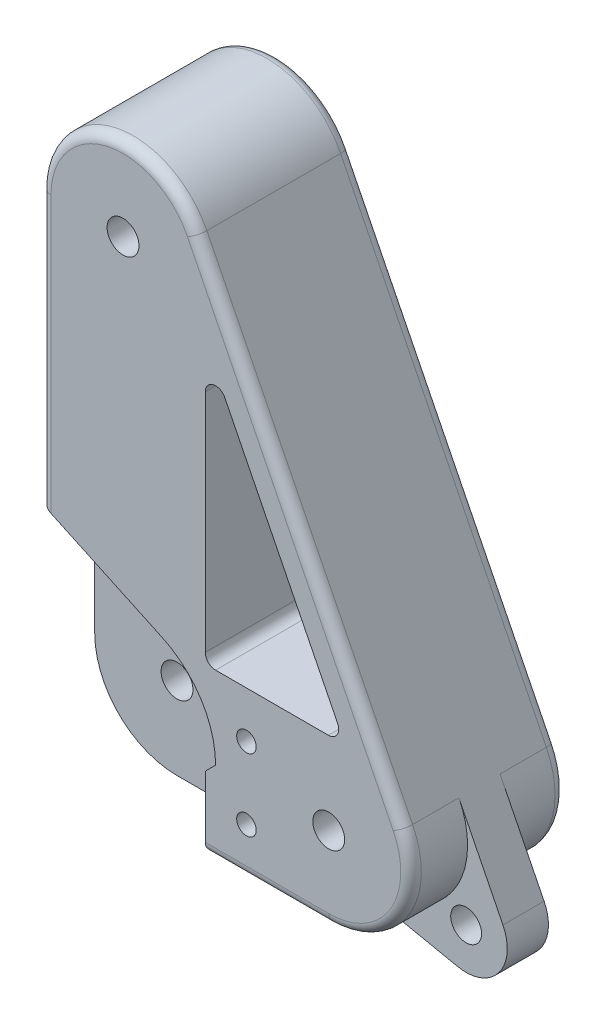
SolidWorks part; units mm, degrees
ref_plane "Front Plane" through (0, 0, 0) normal (0, 0, 1) x (1, 0, 0)
ref_plane "Top Plane" through (0, 0, 0) normal (0, 1, 0) x (1, 0, 0)
ref_plane "Right Plane" through (0, 0, 0) normal (1, 0, 0) x (0, 0, -1)
sketch "Sketch1" plane through (0, 0, 0) normal (0, 0, 1) x (1, 0, 0)
  line L2 (20, -8) -> (0, -8)
  line L3 (-8, 40) -> (-8, 0)
  line L4 (7.1554, 43.5777) -> (27.1554, 3.5777)
  circle A0 centre (0, 0) radius 1.55
  circle A1 centre (20, 0) radius 1.55
  circle A2 centre (0, 40) radius 1.55
  arc A3 (-8, 40) -> (7.1554, 43.5777) centre (0, 40) cw
  arc A4 (-8, 0) -> (0, -8) centre (0, 0) ccw
  arc A5 (27.1554, 3.5777) -> (20, -8) centre (20, 0) cw
  dimension "D1" = 3.1
  dimension "D2" = 8
  dimension "D3" = 40
  dimension "D5" = 20
extrude "Boss-Extrude1" add sketch "Sketch1" along normal blind 15
fillet "Fillet1" radius 1 6 edges at (26.8052, -4.2058, 0) (10, -8, 0) (-5.6569, -5.6569, 0) (-8, 20, 0) (-1.838, 47.786, 0) (17.1554, 23.5777, 0)
fillet "Fillet2" radius 1 6 edges at (-8, 20, 15) (-5.6569, -5.6569, 15) (10, -8, 15) (26.8052, -4.2058, 15) (-1.838, 47.786, 15) (17.1554, 23.5777, 15)
sketch "Sketch2" plane through (0, 0, 15) normal (0, 0, 1) x (1, 0, 0)
  line L2 (8, -8) -> (-8, -8)
  line L3 (-8, -8) -> (-8, 13.6609)
  line L4 (-8, 13.6609) -> (3.8036, 8.1568)
  line L5 (9, 0) -> (8, -8) construction
  line L6 (8, -8) -> (8, -1)
  line L7 (8, -1) -> (9, 0)
  line L8 (20, -8) -> (0, -8) construction
  line L9 (-8, 0) -> (-8, 40) construction
  arc A3 (3.8036, 8.1568) -> (9, 0) centre (0, 0) cw
  dimension "D1" = 9
  dimension "D2" = 1
  dimension "D3" = 25
  dimension "D4" = 45
extrude "Cut-Extrude1" cut sketch "Sketch2" against normal blind 5.25
ref_plane "Plane1" through (0, 0, 7.5) normal (0, 0, 1) x (1, 0, 0)
mirror "Mirror1" about plane through (0, 0, 7.5) normal (0, 0, 1) of "Cut-Extrude1"
sketch "Sketch3" plane through (0, 0, 7.5) normal (0, 0, 1) x (1, 0, 0)
  line L0 (31.4367, -4.9848) -> (27.1554, 3.5777)
  line L1 (27.1554, 3.5777) -> (14, -8)
  line L2 (7.1554, 43.5777) -> (27.1554, 3.5777) construction
  line L3 (14, -8) -> (27.0511, -10.6912)
  line L5 (20, -8) -> (8, -8) construction
  circle A0 centre (27.859, -6.7736) radius 1.5
  arc A1 (27.0511, -10.6912) -> (31.4367, -4.9848) centre (27.859, -6.7736) ccw
  dimension "D1" = 3
  dimension "D2" = 4
extrude "Boss-Extrude2" add sketch "Sketch3" against normal blind 2 and the other way blind 2
sketch "Sketch4" plane through (0, 0, 0) normal (0, 0, -1) x (-1, 0, 0)
  line L0 (0, 0) -> (-15.2179, 0) construction
  circle A0 centre (-12, 3.5) radius 0.95
  circle A2 centre (-12, -3.5) radius 0.95
  circle A3 centre (0, 0) radius 1.55 construction
  dimension "D1" = 1.9
  dimension "D2" = 7
  dimension "D3" = 12
extrude "Cut-Extrude2" cut sketch "Sketch4" against normal through all
sketch "Sketch5" plane through (0, 0, 0) normal (0, 0, -1) x (-1, 0, 0)
  line L0 (-8, 35.1803) -> (-8, 8)
  line L3 (-8, 8) -> (-20, 8)
  line L4 (-21.6793, 7.8218) -> (-8, 35.1803)
  line L5 (8, 40) -> (8, 13.6609) construction
  line L6 (-27.1554, 3.5777) -> (-7.1554, 43.5777) construction
  arc A3 (-21.6793, 7.8218) -> (-20, 8) centre (-20, 0) cw
  circle A4 centre (0, 0) radius 1.55 construction
  dimension "D4" = 8
  dimension "D1" = 16
  dimension "D2" = 3
  dimension "D5" = 8
extrude "Cut-Extrude3" cut sketch "Sketch5" against normal through all
fillet "Fillet3" radius 1 3 edges at (8, 35.1803, 7.5) (8, 8, 7.5) (21.6793, 7.8218, 7.5)
